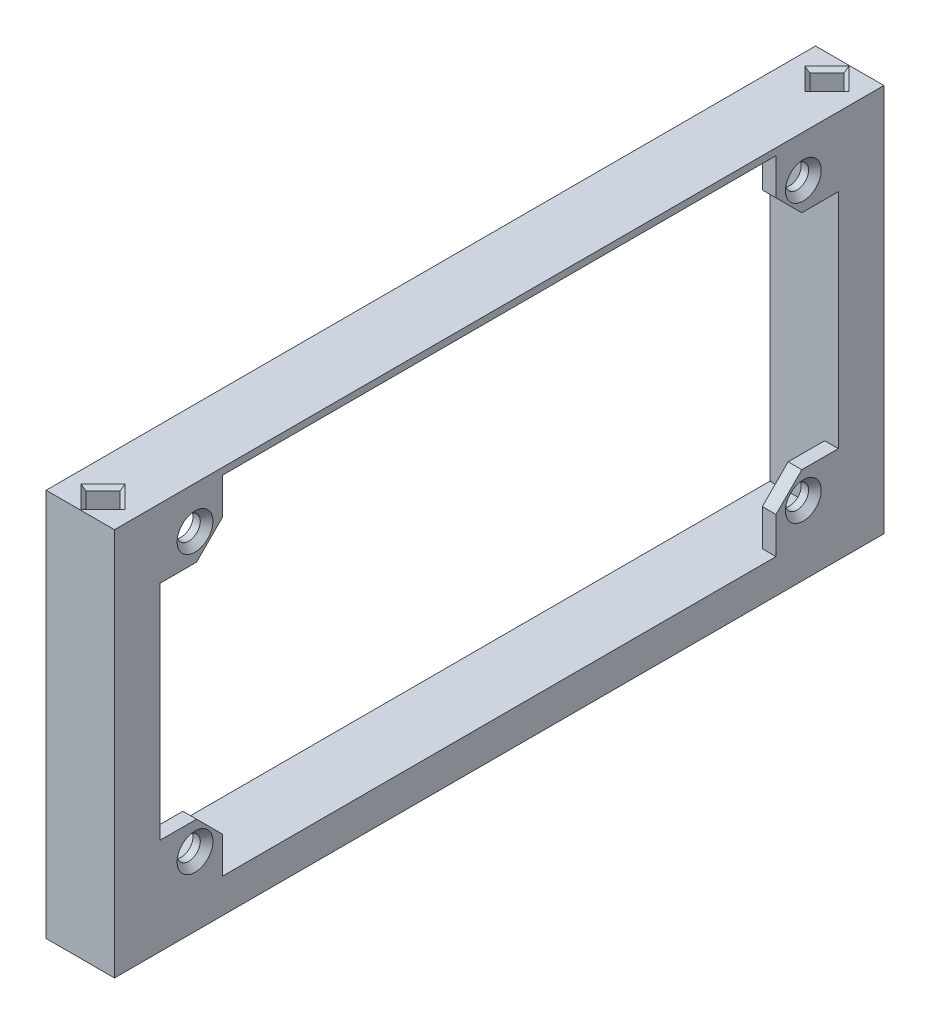
SolidWorks part; units mm, degrees
ref_plane "Front Plane" through (0, 0, 0) normal (0, 0, 1) x (1, 0, 0)
ref_plane "Top Plane" through (0, 0, 0) normal (0, 1, 0) x (1, 0, 0)
ref_plane "Right Plane" through (0, 0, 0) normal (1, 0, 0) x (0, 0, -1)
ref_plane "Plane1" through (-2.54, 0, 0) normal (1, 0, 0) x (0, 0, -1)
sketch "Sketch4" plane through (-2.54, 0, 0) normal (1, 0, 0) x (0, 0, -1)
  line L0 (62.5, 31.75) -> (-62.5, 31.75) construction
  line L1 (62.5, 31.75) -> (62.5, -31.75) construction
  line L2 (62.5, -31.75) -> (-62.5, -31.75) construction
  line L3 (-62.5, 31.75) -> (-62.5, -31.75) construction
  line L4 (-62.5, 25.75) -> (-56.5, 25.75) construction
  line L5 (-56.5, 25.75) -> (-56.5, 31.75) construction
  line L6 (56.5, -31.75) -> (56.5, -25.75) construction
  line L7 (56.5, -25.75) -> (62.5, -25.75) construction
  point P9 (-56.5, -25.75)
  point P11 (56.5, 25.75)
  point P12 (56.5, 0)
  point P13 (-56.5, 0)
  point P14 (56.5, -25.75)
  point P15 (62.5, 0)
  point P16 (-56.5, 25.75)
  point P17 (0, 31.75)
  point P19 (-62.5, 0)
  dimension "D1" = 63.5
  dimension "D2" = 125
  dimension "D3" = 6
sketch "Sketch1" plane through (0, 0, 0) normal (1, 0, 0) x (0, 0, -1)
  line L1 (-71.4667, 33.52) -> (71.4667, 33.52)
  line L2 (-71.4667, 33.52) -> (-71.4667, -38.6)
  line L3 (-71.4667, -38.6) -> (71.4667, -38.6)
  line L4 (71.4667, 33.52) -> (71.4667, -38.6)
  line L5 (-63, 32.25) -> (63, 32.25)
  line L6 (-63, 32.25) -> (-63, -32.25)
  line L7 (-63, -32.25) -> (63, -32.25)
  line L8 (63, 32.25) -> (63, -32.25)
  point P10 (0, 33.52)
  point P11 (-63, 0)
  point P15 (0, -32.25)
  dimension "D1" = 8.4667
  dimension "D2" = 142.9333
  dimension "D3" = 72.12
  dimension "D4" = 1.27
  dimension "D5" = 6.35
extrude "Boss-Extrude1" add sketch "Sketch1" against normal blind 12.7
sketch "Sketch2" plane through (0, 33.52, 0) normal (0, 1, 0) x (1, 0, 0)
  line L0 (-3.175, 67.2333) -> (-6.35, 64.0583)
  line L1 (-3.175, 67.2333) -> (-6.35, 70.4083)
  line L2 (-6.35, 64.0583) -> (-9.525, 67.2333)
  line L3 (-6.35, 70.4083) -> (-9.525, 67.2333)
  line L4 (-3.175, 67.2333) -> (-9.525, 67.2333) construction
  line L5 (-6.35, 64.0583) -> (-6.35, 70.4083) construction
  line L6 (-3.175, -67.2333) -> (-6.35, -70.4083)
  line L7 (-3.175, -67.2333) -> (-6.35, -64.0583)
  line L8 (-6.35, -70.4083) -> (-9.525, -67.2333)
  line L9 (-6.35, -64.0583) -> (-9.525, -67.2333)
  line L10 (-3.175, -67.2333) -> (-9.525, -67.2333) construction
  line L11 (-6.35, -70.4083) -> (-6.35, -64.0583) construction
  line L15 (-12.7, 71.4667) -> (0, 71.4667) construction
  line L16 (-12.7, 71.4667) -> (-12.7, -71.4667) construction
  line L17 (-12.7, -71.4667) -> (0, -71.4667) construction
  point P1 (-6.35, 67.2333)
  point P2 (-6.35, -67.2333)
  dimension "D1" = 6.35
  dimension "D2" = 4.2333
  dimension "D3" = 6.35
  dimension "D4" = 4.2333
extrude "Cut-Extrude1" cut sketch "Sketch2" against normal blind 5.08
sketch "Sketch3" plane through (-12.7, 0, 0) normal (-1, 0, 0) x (0, 0, 1)
  line L0 (70.4083, 25.0533) -> (67.2333, 21.8783)
  line L1 (70.4083, 25.0533) -> (67.2333, 28.2283)
  line L2 (67.2333, 21.8783) -> (64.0583, 25.0533)
  line L3 (67.2333, 28.2283) -> (64.0583, 25.0533)
  line L4 (70.4083, 25.0533) -> (64.0583, 25.0533) construction
  line L5 (67.2333, 21.8783) -> (67.2333, 28.2283) construction
  line L6 (-64.0583, -30.1333) -> (-67.2333, -33.3083)
  line L7 (-64.0583, -30.1333) -> (-67.2333, -26.9583)
  line L8 (-67.2333, -33.3083) -> (-70.4083, -30.1333)
  line L9 (-67.2333, -26.9583) -> (-70.4083, -30.1333)
  line L10 (-64.0583, -30.1333) -> (-70.4083, -30.1333) construction
  line L11 (-67.2333, -33.3083) -> (-67.2333, -26.9583) construction
  line L12 (71.4667, -38.6) -> (-71.4667, -38.6) construction
  line L15 (64.0583, -30.1333) -> (67.2333, -26.9583)
  line L16 (64.0583, -30.1333) -> (67.2333, -33.3083)
  line L17 (67.2333, -26.9583) -> (70.4083, -30.1333)
  line L18 (67.2333, -33.3083) -> (70.4083, -30.1333)
  line L19 (64.0583, -30.1333) -> (70.4083, -30.1333) construction
  line L20 (67.2333, -26.9583) -> (67.2333, -33.3083) construction
  line L23 (-71.4667, 33.52) -> (71.4667, 33.52) construction
  line L24 (71.4667, 33.52) -> (71.4667, -38.6) construction
  line L25 (-71.4667, -38.6) -> (-71.4667, 33.52) construction
  point P1 (67.2333, 25.0533)
  point P2 (-67.2333, -30.1333)
  point P18 (67.2333, -30.1333)
  dimension "D1" = 6.35
  dimension "D2" = 8.4667
  dimension "D3" = 8.4667
  dimension "D4" = 4.2333
  dimension "D5" = 4.2333
extrude "Cut-Extrude2" cut sketch "Sketch3" against normal blind 5.08
sketch "Sketch5" plane through (0, -38.6, 0) normal (0, -1, 0) x (1, 0, 0)
  line L0 (-4.2333, -70.4083) -> (-7.4083, -67.2333)
  line L1 (-4.2333, -70.4083) -> (-1.0583, -67.2333)
  line L2 (-7.4083, -67.2333) -> (-4.2333, -64.0583)
  line L3 (-1.0583, -67.2333) -> (-4.2333, -64.0583)
  line L4 (-4.2333, -70.4083) -> (-4.2333, -64.0583) construction
  line L5 (-7.4083, -67.2333) -> (-1.0583, -67.2333) construction
  line L6 (-4.2333, 64.0583) -> (-7.4083, 67.2333)
  line L7 (-4.2333, 64.0583) -> (-1.0583, 67.2333)
  line L8 (-7.4083, 67.2333) -> (-4.2333, 70.4083)
  line L9 (-1.0583, 67.2333) -> (-4.2333, 70.4083)
  line L10 (-4.2333, 64.0583) -> (-4.2333, 70.4083) construction
  line L11 (-7.4083, 67.2333) -> (-1.0583, 67.2333) construction
  line L12 (0, 71.4667) -> (0, -71.4667) construction
  line L13 (-12.7, -71.4667) -> (0, -71.4667) construction
  line L14 (-12.7, 71.4667) -> (0, 71.4667) construction
  point P1 (-4.2333, -67.2333)
  point P2 (-4.2333, 67.2333)
  dimension "D1" = 4.2333
  dimension "D2" = 4.2333
  dimension "D3" = 6.35
  dimension "D4" = 4.2333
extrude "Cut-Extrude3" cut sketch "Sketch5" against normal blind 5.08
chamfer "Chamfer1" distance 0.635 angle 45 56 edges at (-7.62, -28.5458, 65.6458) (-7.62, -28.5458, 68.8208) (-7.62, -31.7208, 68.8208) (-7.62, -31.7208, 65.6458) (-7.62, -31.7208, -65.6458) (-7.62, -31.7208, -68.8208) (-7.62, -28.5458, -68.8208) (-7.62, -28.5458, -65.6458) (-4.7625, 28.44, 68.8208) (-7.9375, 28.44, 68.8208) (-7.9375, 28.44, 65.6458) (-4.7625, 28.44, 65.6458) (-4.7625, 28.44, -65.6458) (-7.9375, 28.44, -65.6458) (-7.9375, 28.44, -68.8208) (-4.7625, 28.44, -68.8208) (-7.62, 23.4658, 68.8208) (-7.62, 23.4658, 65.6458) (-7.62, 26.6408, 65.6458) (-7.62, 26.6408, 68.8208) (-7.9375, 33.52, 68.8208) (-4.7625, 33.52, 68.8208) (-7.9375, 33.52, 65.6458) (-4.7625, 33.52, 65.6458) (-7.9375, 33.52, -68.8208) (-4.7625, 33.52, -68.8208) (-4.7625, 33.52, -65.6458) (-7.9375, 33.52, -65.6458) (-12.7, -31.7208, 65.6458) (-12.7, -28.5458, 65.6458) (-12.7, -28.5458, 68.8208) (-12.7, -31.7208, 68.8208) (-12.7, -28.5458, -65.6458) (-12.7, -28.5458, -68.8208) (-12.7, -31.7208, -68.8208) (-12.7, -31.7208, -65.6458) (-12.7, 26.6408, 68.8208) (-12.7, 26.6408, 65.6458) (-12.7, 23.4658, 65.6458) (-12.7, 23.4658, 68.8208) (-5.8208, -33.52, -68.8208) (-5.8208, -33.52, -65.6458) (-2.6458, -33.52, -65.6458) (-2.6458, -33.52, -68.8208) (-5.8208, -33.52, 65.6458) (-5.8208, -33.52, 68.8208) (-2.6458, -33.52, 68.8208) (-2.6458, -33.52, 65.6458) (-2.6458, -38.6, -65.6458) (-5.8208, -38.6, -65.6458) (-5.8208, -38.6, -68.8208) (-2.6458, -38.6, -68.8208) (-2.6458, -38.6, 68.8208) (-5.8208, -38.6, 68.8208) (-5.8208, -38.6, 65.6458) (-2.6458, -38.6, 65.6458)
sketch "Sketch6" plane through (0, -32.25, 0) normal (0, 1, 0) x (1, 0, 0)
  line L1 (-8.4667, -55.126) -> (-12.7, -55.126)
  line L2 (-12.7, -63) -> (-12.7, 63) construction
  line L3 (-12.7, -55.126) -> (-12.7, -63)
  line L4 (-12.7, -63) -> (-8.4667, -63)
  line L5 (-12.7, -63) -> (-12.7, 63) construction
  arc A0 (-8.4667, -63) -> (-8.4667, -55.126) centre (-8.4667, -59.063) ccw
  point P1 (-12.7, -63)
  point P10 (-8.4667, -61.5876)
  point P11 (-12.7, -62.8503)
  point P12 (-12.7, -61.4681)
  dimension "D1" = 7.874
  dimension "D2" = 4.2333
extrude "Cut-Extrude4" cut sketch "Sketch6" against normal blind 2.54
sketch "Sketch7" plane through (0, -34.79, 0) normal (0, 1, 0) x (1, 0, 0)
  arc A0 (-8.4667, -63) -> (-8.4667, -55.126) centre (-8.4667, -59.063) ccw construction
  point P0 (-8.4667, -59.063)
hole_wizard "#18 (0.1695) Diameter Hole1" positions "Sketch7" profile "Sketch8" hole size "#18" standard "ANSI Inch"
sketch "Sketch8" plane through (-8.4667, -34.79, 59.063) normal (1, 0, 0) x (0, 0, 1)
  line L0 (0, 0) -> (0, 3.81)
  line L1 (0, 3.81) -> (2.1526, 3.81)
  line L2 (2.1526, 3.81) -> (2.1526, 0.635)
  line L3 (2.1526, 0.635) -> (2.7876, 0)
  line L5 (2.7876, 0) -> (0, 0)
  line L6 (-2.1526, 0.635) -> (-2.7876, 0) construction
  line L11 (0, -6.35) -> (0, 107.95) construction
  dimension "Thru Hole Dia." = 4.3053
  dimension "Thru Hole Depth" = 3.81
  dimension "Near C'Sink Dia." = 5.5753
  dimension "Near C'Sink Angle" = 90
sketch "Sketch9" plane through (0, 0, 0) normal (1, 0, 0) x (0, 0, -1)
  line L0 (-63, 20.67) -> (-56.2166, 20.67)
  line L1 (-63, 32.25) -> (-63, -32.25) construction
  line L2 (-56.2166, 20.67) -> (-51.42, 25.4666)
  line L3 (-51.42, 25.4666) -> (-51.42, 32.25)
  line L4 (63, 32.25) -> (-63, 32.25) construction
  line L5 (-63, -20.67) -> (-56.2166, -20.67)
  line L6 (-56.2166, -20.67) -> (-51.42, -25.4666)
  line L7 (-51.42, -25.4666) -> (-51.42, -32.25)
  line L8 (-63, -32.25) -> (63, -32.25) construction
  line L9 (51.42, -32.25) -> (51.42, -25.4666)
  line L10 (51.42, -25.4666) -> (56.2166, -20.67)
  line L11 (56.2166, -20.67) -> (63, -20.67)
  line L12 (63, -32.25) -> (63, 32.25) construction
  line L13 (51.42, 32.25) -> (51.42, 25.4666)
  line L14 (51.42, 25.4666) -> (56.2166, 20.67)
  line L15 (56.2166, 20.67) -> (63, 20.67)
  line L16 (-63, -20.67) -> (-63, -32.25)
  line L17 (-63, 32.25) -> (-51.42, 32.25)
  line L18 (-63, 32.25) -> (-63, 20.67)
  line L19 (-63, -32.25) -> (-51.42, -32.25)
  line L20 (63, 32.25) -> (63, 20.67)
  line L21 (51.42, 32.25) -> (63, 32.25)
  line L22 (51.42, -32.25) -> (63, -32.25)
  line L23 (63, -20.67) -> (63, -32.25)
  dimension "D1" = 5.08
  dimension "D2" = 45
extrude "Boss-Extrude2" add sketch "Sketch9" against normal blind 2.54
sketch "Sketch10" plane through (0, 0, 0) normal (1, 0, 0) x (0, 0, -1)
  point P0 (-56.5, 25.75)
  point P1 (56.5, 25.75)
  point P3 (56.5, -25.75)
  point P5 (-56.5, -25.75)
hole_wizard "#6 Clearance Hole1" positions "Sketch10" profile "Sketch11" hole size "#6" standard "ANSI Inch" end condition through all
sketch "Sketch11" plane through (0, 25.75, 56.5) normal (0, 1, 0) x (0, 0, -1)
  line L0 (0, 0) -> (0, 12.7)
  line L1 (0, 12.7) -> (2.1526, 12.7)
  line L2 (2.1526, 12.7) -> (2.1526, 1.1747)
  line L3 (2.1526, 1.1747) -> (3.3274, 0)
  line L5 (3.3274, 0) -> (0, 0)
  line L6 (-2.1526, 1.1747) -> (-3.3274, 0) construction
  line L11 (0, -6.35) -> (0, 107.95) construction
  dimension "Thru Hole Dia." = 4.3053
  dimension "Thru Hole Depth" = 12.7
  dimension "Near C'Sink Dia." = 6.6548
  dimension "Near C'Sink Angle" = 90
